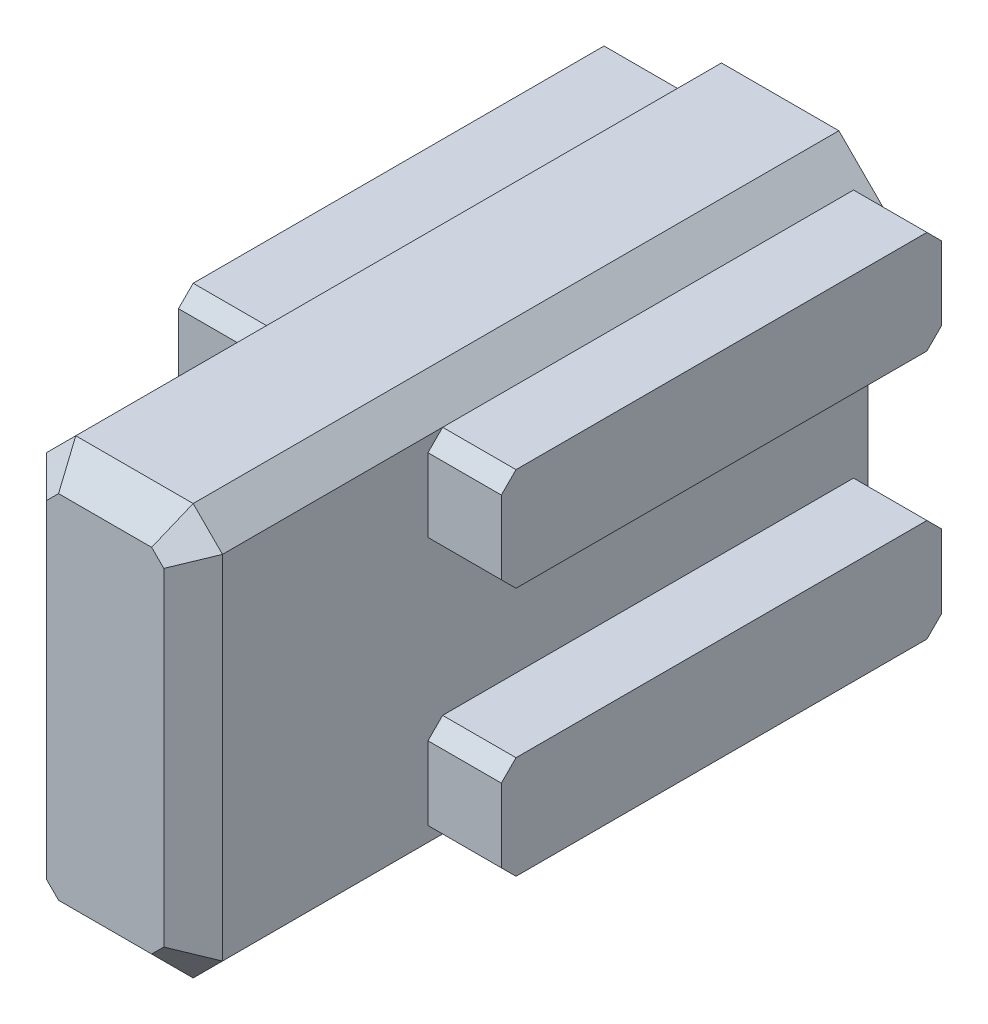
SolidWorks part; units mm, degrees
ref_plane "정면" through (0, 0, 0) normal (0, 0, 1) x (1, 0, 0)
ref_plane "윗면" through (0, 0, 0) normal (0, 1, 0) x (1, 0, 0)
ref_plane "우측면" through (0, 0, 0) normal (1, 0, 0) x (0, 0, -1)
sketch "스케치1" plane through (0, 0, 0) normal (0, 0, 1) x (1, 0, 0)
  line L1 (-3, 7) -> (3, 7)
  line L2 (-3, 7) -> (-3, -7)
  line L3 (-3, -7) -> (3, -7)
  line L4 (3, 7) -> (3, -7)
  line L5 (-3, 7) -> (3, -7) construction
  line L6 (-3, -7) -> (3, 7) construction
  point P0 (0, 0)
  dimension "D1" = 6
  dimension "D2" = 14
extrude "보스-돌출1" add sketch "스케치1" along normal blind 23
chamfer "모따기1" distance 1 angle 45 4 edges at (-3, -7, 11.5) (3, -7, 11.5) (3, 7, 11.5) (-3, 7, 11.5)
sketch "스케치2" plane through (0, 0, 0) normal (0, 0, 1) x (1, 0, 0)
  line L0 (3, -6) -> (3, 6) construction
  line L1 (3, 6) -> (5.5, 6)
  line L2 (3, 6) -> (3, 2.5)
  line L3 (3, 2.5) -> (5.5, 2.5)
  line L4 (5.5, 6) -> (5.5, 2.5)
  line L5 (0, 7.9623) -> (0, 0) construction
  line L6 (3, -2.5) -> (5.5, -2.5)
  line L7 (3, -2.5) -> (3, -6)
  line L8 (3, -6) -> (5.5, -6)
  line L9 (5.5, -2.5) -> (5.5, -6)
  line L10 (-5.5, -2.5) -> (-5.5, -6)
  line L11 (-3, -6) -> (-5.5, -6)
  line L12 (-3, -2.5) -> (-3, -6)
  line L13 (-5.5, 6) -> (-5.5, 2.5)
  line L14 (-3, 2.5) -> (-5.5, 2.5)
  line L15 (-3, 6) -> (-3, 2.5)
  line L16 (-3, 6) -> (-5.5, 6)
  line L17 (-3, -2.5) -> (-5.5, -2.5)
  line L18 (3, 2.5) -> (3, -2.5) construction
  line L19 (3, 0) -> (0, 0) construction
  dimension "D1" = 2.5
  dimension "D2" = 3.5
  dimension "D3" = 3.5
  dimension "D4" = 5
extrude "보스-돌출2" add sketch "스케치2" along normal blind 15
chamfer "모따기2" distance 0.5 angle 45 16 edges at (-4.25, -2.5, 15) (-4.25, 2.5, 15) (-4.25, 6, 15) (-4.25, 2.5, 0) (-4.25, 6, 0) (-4.25, -6, 0) (4.25, -2.5, 0) (4.25, -2.5, 15) (4.25, -6, 0) (4.25, -6, 15) (4.25, 2.5, 15) (4.25, 6, 0)
chamfer "모따기3" distance 1 angle 45 8 edges at (-2.5, 6.5, 23) (0, 7, 23) (2.5, 6.5, 23) (3, 0, 23) (2.5, -6.5, 23) (0, -7, 23) (-2.5, -6.5, 23) (-3, 0, 23)
sketch "스케치3" plane through (0, 0, 0) normal (0, 0, -1) x (-1, 0, 0)
  line L0 (0, 3.5) -> (0, 0) construction
  circle A0 centre (0, 3.5) radius 2.35
  dimension "D1" = 4.7
  dimension "D2" = 3.5
extrude "컷-돌출1" cut sketch "스케치3" against normal blind 5
